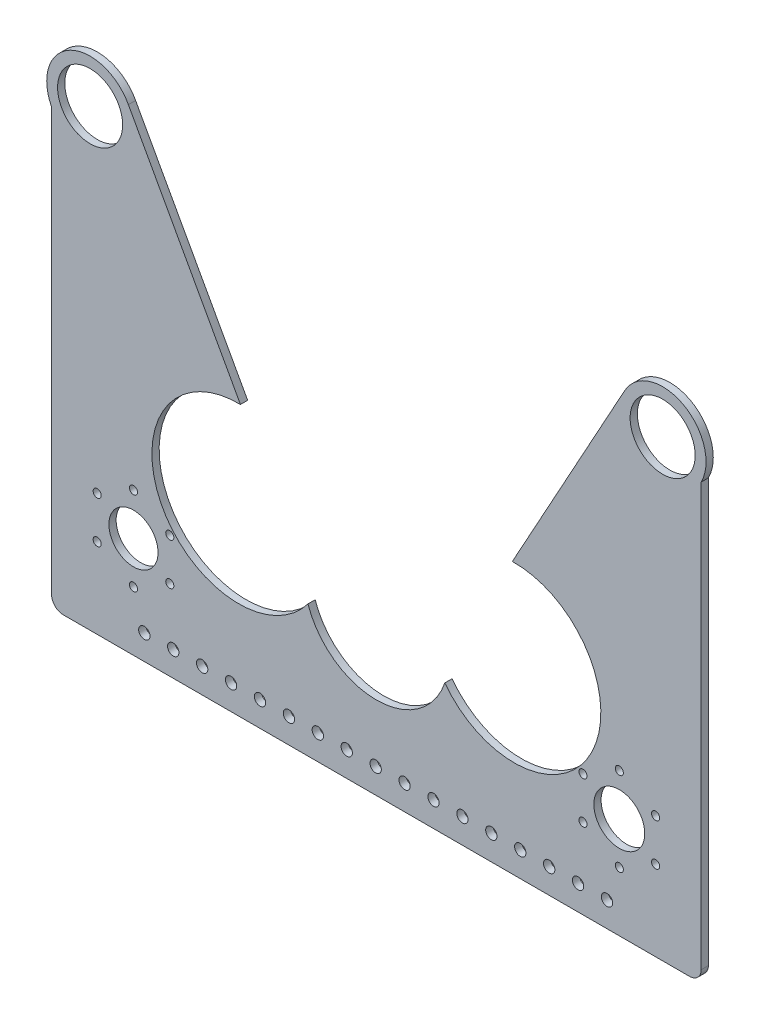
SolidWorks part; units mm, degrees
ref_plane "Front Plane" through (0, 0, 0) normal (0, 0, 1) x (1, 0, 0)
ref_plane "Top Plane" through (0, 0, 0) normal (0, 1, 0) x (1, 0, 0)
ref_plane "Right Plane" through (0, 0, 0) normal (1, 0, 0) x (0, 0, -1)
sketch "Sketch2" plane through (0, 0, 0) normal (0, 0, 1) x (1, 0, 0)
  line L0 (-106.68, -1085.9159) -> (-106.68, 48914.0841) construction
  line L1 (142.6324, 122.4629) -> (142.6324, -29.9371)
  line L2 (106.68, -1098.4025) -> (106.68, 48901.5975) construction
  line L3 (31.75, 0) -> (108.9183, 140.209)
  line L4 (0, -1082.0685) -> (0, 48917.9315) construction
  line L5 (-106.68, -44.45) -> (106.68, -44.45) construction
  line L7 (0, -31.75) -> (106.68, -31.75) construction
  line L9 (-31.75, 0) -> (-108.9183, 140.209)
  line L10 (31.75, 0) -> (108.9183, 140.209)
  line L22 (-142.6324, -57.15) -> (-142.6324, -63.0286)
  line L33 (-106.68, -31.75) -> (0, -31.75) construction
  line L34 (-142.6324, 122.4629) -> (-142.6324, -29.9371)
  line L36 (-261.1394, 46.2048) -> (-243.4617, 46.2048) construction
  line L37 (-243.4617, 46.2048) -> (-243.4617, 28.5272) construction
  line L41 (-238.3305, 62.766) -> (-266.2705, 62.766) construction
  line L42 (-233.2505, 57.686) -> (-233.2505, 17.046) construction
  line L43 (-261.1394, 46.2048) -> (-261.1394, 28.5272) construction
  line L44 (-261.1394, 28.5272) -> (-243.4617, 28.5272) construction
  line L45 (-238.3305, 11.966) -> (-266.2705, 11.966) construction
  line L46 (-271.3505, 57.686) -> (-271.3505, 17.046) construction
  line L47 (-233.2505, 62.766) -> (-271.3505, 11.966) construction
  line L48 (-125.73, 3.175) -> (-125.73, -22.225) construction
  line L49 (-1101.9372, -9.525) -> (48898.0628, -9.525) construction
  line L50 (-233.2505, 11.966) -> (-271.3505, 62.766) construction
  line L51 (-239.6005, 56.416) -> (-239.6005, 18.316) construction
  line L52 (-265.0005, 56.416) -> (-239.6005, 56.416) construction
  line L53 (-125.73, 3.175) -> (-106.68, 3.175) construction
  line L54 (-142.6324, -57.15) -> (142.6324, -57.15) construction
  line L55 (-142.6324, -29.9371) -> (-142.6324, -57.15)
  line L56 (142.6324, -29.9371) -> (142.6324, -57.15)
  line L57 (-137.5524, -68.1086) -> (137.5524, -68.1086)
  line L58 (142.6324, -63.0286) -> (142.6324, -57.15)
  arc A0 (-31.75, 0) -> (31.75, 0) centre (0, 0) ccw
  arc A1 (-108.9183, 140.209) -> (-142.6324, 122.4629) centre (-125.7268, 131.2438) ccw
  circle A2 centre (-60.4845, 12.7) radius 14.2875
  arc A3 (31.75, 0) -> (0, 31.75) centre (0, 0) ccw construction
  arc A4 (0, 31.75) -> (-31.75, 0) centre (0, 0) ccw construction
  arc A5 (137.5524, -68.1086) -> (142.6324, -63.0286) centre (137.5524, -63.0286) ccw
  arc A6 (-142.6324, -63.0286) -> (-137.5524, -68.1086) centre (-137.5524, -63.0286) ccw
  circle A7 centre (-125.7268, 131.2438) radius 14.2875
  circle A9 centre (-60.4845, 12.7) radius 19.05 construction
  circle A10 centre (60.4845, 12.7) radius 19.05 construction
  arc A11 (108.9183, 140.209) -> (142.6324, 122.4629) centre (125.7268, 131.2438) cw
  circle A12 centre (125.7268, 131.2438) radius 14.2875
  circle A34 centre (-101.9175, -57.15) radius 2.4892
  arc A40 (-142.6324, 122.4629) -> (-108.9183, 140.209) centre (-125.7268, 131.2438) ccw construction
  arc A41 (142.6324, 122.4629) -> (108.9183, 140.209) centre (125.7268, 131.2438) cw construction
  circle A42 centre (60.4845, 12.7) radius 14.2875
  circle A43 centre (-89.2175, -57.15) radius 2.4892
  circle A44 centre (-76.5175, -57.15) radius 2.4892
  circle A45 centre (-63.8175, -57.15) radius 2.4892
  circle A46 centre (-51.1175, -57.15) radius 2.4892
  circle A47 centre (-38.4175, -57.15) radius 2.4892
  circle A48 centre (-25.7175, -57.15) radius 2.4892
  circle A49 centre (-13.0175, -57.15) radius 2.4892
  circle A50 centre (-0.3175, -57.15) radius 2.4892
  circle A51 centre (12.3825, -57.15) radius 2.4892
  circle A52 centre (25.0825, -57.15) radius 2.4892
  circle A53 centre (37.7825, -57.15) radius 2.4892
  circle A54 centre (50.4825, -57.15) radius 2.4892
  circle A55 centre (63.1825, -57.15) radius 2.4892
  circle A56 centre (75.8825, -57.15) radius 2.4892
  circle A57 centre (88.5825, -57.15) radius 2.4892
  circle A58 centre (101.2825, -57.15) radius 2.4892
  circle A69 centre (-106.68, -23.6586) radius 10.795
  arc A100 (-260.1552, 27.7564) -> (-262.1235, 29.2979) centre (-261.1394, 28.5272) ccw construction
  arc A101 (-262.1235, 29.2979) -> (-260.1552, 27.7564) centre (-261.1394, 28.5272) ccw construction
  arc A102 (-244.4458, 29.2979) -> (-242.4776, 27.7564) centre (-243.4617, 28.5272) ccw construction
  arc A103 (-242.4776, 27.7564) -> (-244.4458, 29.2979) centre (-243.4617, 28.5272) ccw construction
  arc A104 (-242.4776, 45.4341) -> (-244.4458, 46.9756) centre (-243.4617, 46.2048) ccw construction
  arc A105 (-244.4458, 46.9756) -> (-242.4776, 45.4341) centre (-243.4617, 46.2048) ccw construction
  arc A106 (-262.1235, 46.9756) -> (-260.1552, 45.4341) centre (-261.1394, 46.2048) ccw construction
  arc A107 (-260.1552, 45.4341) -> (-262.1235, 46.9756) centre (-261.1394, 46.2048) ccw construction
  circle A108 centre (-252.3005, 37.366) radius 7.3172 construction
  circle A109 centre (-265.0005, 56.416) radius 3.175 construction
  circle A110 centre (-239.6005, 56.416) radius 3.175 construction
  circle A111 centre (-239.6005, 18.316) radius 3.175 construction
  circle A112 centre (-265.0005, 18.316) radius 3.175 construction
  arc A113 (-266.2705, 11.966) -> (-271.3505, 17.046) centre (-266.2705, 17.046) cw construction
  arc A114 (-233.2505, 17.046) -> (-238.3305, 11.966) centre (-238.3305, 17.046) cw construction
  arc A115 (-238.3305, 62.766) -> (-233.2505, 57.686) centre (-238.3305, 57.686) cw construction
  arc A116 (-266.2705, 62.766) -> (-271.3505, 57.686) centre (-266.2705, 57.686) ccw construction
  circle A123 centre (106.68, -23.6586) radius 11.176
  circle A138 centre (-106.68, -5.2436) radius 1.778
  circle A139 centre (-90.7321, -14.4511) radius 1.778
  circle A140 centre (-90.7321, -32.8661) radius 1.778
  circle A147 centre (-60.4845, 12.7) radius 38.1
  circle A148 centre (60.4845, 12.7) radius 38.1
  circle A149 centre (-106.68, -42.0736) radius 1.778
  circle A150 centre (-122.6279, -32.8661) radius 1.778
  circle A151 centre (-122.6279, -14.4511) radius 1.778
  circle A153 centre (106.68, -5.2436) radius 1.778
  circle A154 centre (122.6279, -14.4511) radius 1.778
  circle A155 centre (122.6279, -32.8661) radius 1.778
  circle A156 centre (106.68, -42.0736) radius 1.778
  circle A157 centre (90.7321, -32.8661) radius 1.778
  circle A158 centre (90.7321, -14.4511) radius 1.778
  point P87 (-106.68, -30.0086)
  point P90 (-106.68, -23.6586)
  point P107 (107.6224, -29.9371)
  point P148 (-106.68, -30.0086)
  point P152 (106.68, -29.9371)
  point P154 (-125.73, -9.525)
  point P155 (106.68, -23.6586)
  dimension "D7" = 131.2438
  dimension "D8" = 101.9175
  dimension "D9" = 25.4
  dimension "D3" = 44.45
  dimension "D14" = 106.68
  dimension "D17" = 38.1
  dimension "D5" = 5.08
  dimension "D15" = 31.75
  dimension "D16" = 28.575
  dimension "D18" = 28.575
  dimension "D19" = 19.05
  dimension "D23" = 6
  dimension "D21" = 125.7268
  dimension "D33" = 6.35
  dimension "D35" = 8.8388
  dimension "D37" = 8.8388
  dimension "D34" = 6.35
  dimension "D36" = 1.25
  dimension "D38" = 5.08
  dimension "D11" = 6
  dimension "D12" = 21.59
  dimension "D1" = 28.828
  dimension "D6" = 10.9586
  dimension "D10" = 17
  dimension "D13" = 44.45
  dimension "D20" = 142.6324
  dimension "D25" = 152.4
  dimension "D26" = 12.7
  dimension "D32" = 6.35
  dimension "D29" = 17.6777
  dimension "D30" = 50.8
  dimension "D31" = 38.1
  dimension "D39" = 25.4
  dimension "D40" = 38.1
  dimension "D41" = 16.9024
extrude "Boss-Extrude1" add sketch "Sketch2" along normal blind 3.175
sketch "Sketch3" plane through (0, 0, 3.175) normal (0, 0, -1) x (-1, 0, 0)
  line L0 (-125.7268, 150.2938) -> (49874.2732, 150.2938) construction
  line L1 (-144.7768, 131.2438) -> (-144.7768, 50131.2438) construction
  point P4 (-144.7768, 150.2938)
sketch "Sketch4" plane through (0, 0, 0) normal (0, 0, -1) x (-1, 0, 0)
  line L5 (-142.6324, 122.4629) -> (-142.6324, -63.0286)
  line L6 (-137.5524, -68.1086) -> (137.5524, -68.1086)
  line L7 (142.6324, -63.0286) -> (142.6324, 122.4629)
  line L8 (108.9183, 140.209) -> (59.7049, 50.792)
  line L9 (-59.7049, 50.792) -> (-108.9183, 140.209)
  line L10 (-142.6324, 122.4629) -> (-142.6324, -63.0286)
  line L11 (-137.5524, -68.1086) -> (137.5524, -68.1086)
  line L12 (142.6324, -63.0286) -> (142.6324, 122.4629)
  line L13 (108.9183, 140.209) -> (59.7049, 50.792)
  line L14 (-59.7049, 50.792) -> (-108.9183, 140.209)
  circle A0 centre (-125.7268, 131.2438) radius 14.2875 construction
  arc A5 (-108.9183, 140.209) -> (-142.6324, 122.4629) centre (-125.7268, 131.2438) ccw
  arc A6 (-142.6324, -63.0286) -> (-137.5524, -68.1086) centre (-137.5524, -63.0286) ccw
  arc A7 (137.5524, -68.1086) -> (142.6324, -63.0286) centre (137.5524, -63.0286) ccw
  arc A8 (142.6324, 122.4629) -> (108.9183, 140.209) centre (125.7268, 131.2438) ccw
  arc A9 (-30.0569, -10.2296) -> (30.0569, -10.2296) centre (0, 0) ccw
  arc A10 (-108.9183, 140.209) -> (-142.6324, 122.4629) centre (-125.7268, 131.2438) ccw
  arc A11 (-142.6324, -63.0286) -> (-137.5524, -68.1086) centre (-137.5524, -63.0286) ccw
  arc A12 (137.5524, -68.1086) -> (142.6324, -63.0286) centre (137.5524, -63.0286) ccw
  arc A13 (142.6324, 122.4629) -> (108.9183, 140.209) centre (125.7268, 131.2438) ccw
  arc A14 (-30.0569, -10.2296) -> (30.0569, -10.2296) centre (0, 0) ccw
  arc A18 (-59.7049, 50.792) -> (-30.0569, -10.2296) centre (-60.4845, 12.7) ccw
  arc A19 (-59.7049, 50.792) -> (-30.0569, -10.2296) centre (-60.4845, 12.7) ccw
  arc A20 (30.0569, -10.2296) -> (59.7049, 50.792) centre (60.4845, 12.7) ccw
  circle A21 centre (125.7268, 131.2438) radius 14.2875 construction
  circle A22 centre (60.4845, 12.7) radius 14.2875 construction
  circle A23 centre (101.9175, -57.15) radius 2.4892 construction
  circle A24 centre (89.2175, -57.15) radius 2.4892 construction
  circle A25 centre (76.5175, -57.15) radius 2.4892 construction
  circle A26 centre (63.8175, -57.15) radius 2.4892 construction
  circle A27 centre (51.1175, -57.15) radius 2.4892 construction
  circle A28 centre (38.4175, -57.15) radius 2.4892 construction
  circle A29 centre (25.7175, -57.15) radius 2.4892 construction
  circle A30 centre (13.0175, -57.15) radius 2.4892 construction
  circle A31 centre (0.3175, -57.15) radius 2.4892 construction
  circle A32 centre (-12.3825, -57.15) radius 2.4892 construction
  circle A33 centre (-25.0825, -57.15) radius 2.4892 construction
  circle A34 centre (-37.7825, -57.15) radius 2.4892 construction
  circle A35 centre (-50.4825, -57.15) radius 2.4892 construction
  circle A36 centre (-63.1825, -57.15) radius 2.4892 construction
  circle A37 centre (-75.8825, -57.15) radius 2.4892 construction
  circle A38 centre (-88.5825, -57.15) radius 2.4892 construction
  circle A39 centre (-101.2825, -57.15) radius 2.4892 construction
  circle A40 centre (-60.4845, 12.7) radius 14.2875 construction
  circle A51 centre (125.7268, 131.2438) radius 14.2875
  circle A52 centre (60.4845, 12.7) radius 14.2875
  circle A53 centre (101.9175, -57.15) radius 2.4892
  circle A54 centre (89.2175, -57.15) radius 2.4892
  circle A55 centre (76.5175, -57.15) radius 2.4892
  circle A56 centre (63.8175, -57.15) radius 2.4892
  circle A57 centre (51.1175, -57.15) radius 2.4892
  circle A58 centre (38.4175, -57.15) radius 2.4892
  circle A59 centre (25.7175, -57.15) radius 2.4892
  circle A60 centre (13.0175, -57.15) radius 2.4892
  circle A61 centre (0.3175, -57.15) radius 2.4892
  circle A62 centre (-12.3825, -57.15) radius 2.4892
  circle A63 centre (-25.0825, -57.15) radius 2.4892
  circle A64 centre (-37.7825, -57.15) radius 2.4892
  circle A65 centre (-50.4825, -57.15) radius 2.4892
  circle A66 centre (-63.1825, -57.15) radius 2.4892
  circle A67 centre (-75.8825, -57.15) radius 2.4892
  circle A68 centre (-88.5825, -57.15) radius 2.4892
  circle A69 centre (-101.2825, -57.15) radius 2.4892
  circle A70 centre (-60.4845, 12.7) radius 14.2875
  circle A71 centre (-125.7268, 131.2438) radius 14.2875
  arc A72 (30.0569, -10.2296) -> (59.7049, 50.792) centre (60.4845, 12.7) ccw
  dimension "D1" = 0
